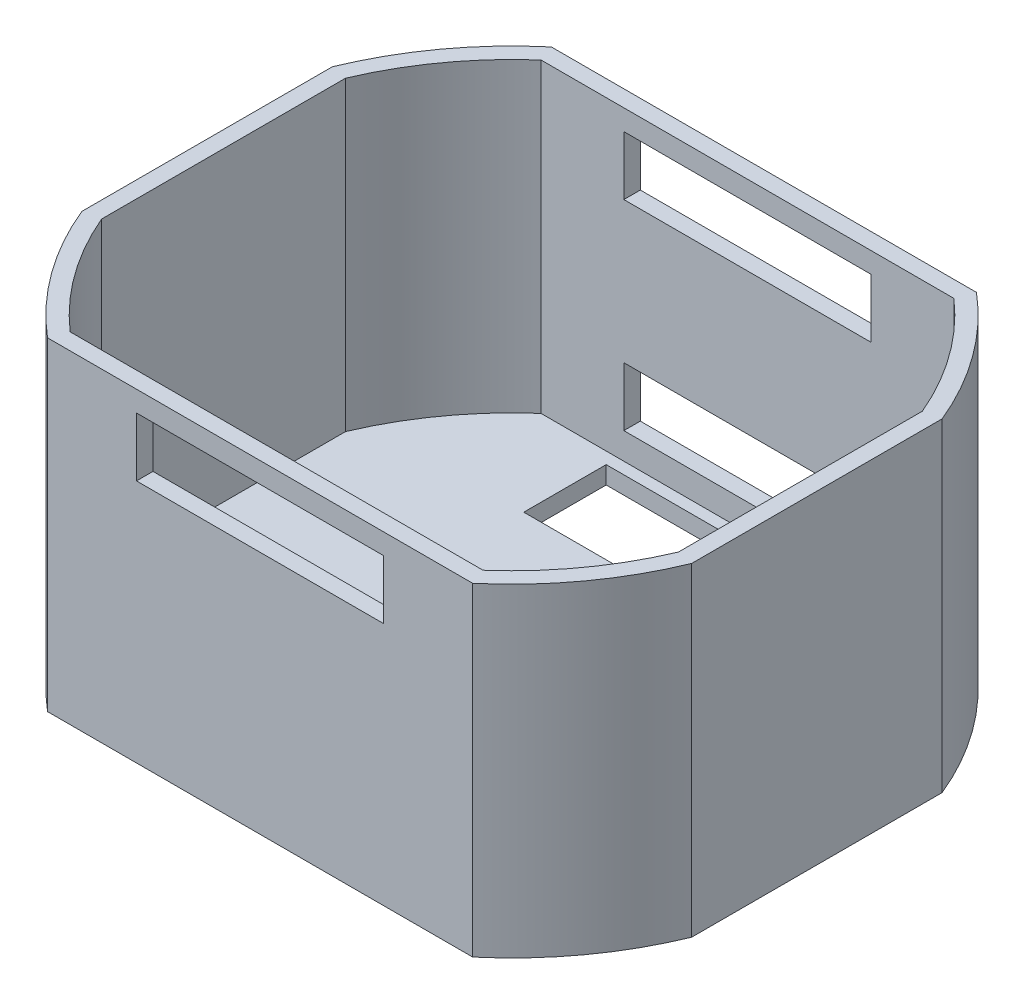
SolidWorks part; units mm, degrees
ref_plane "Front Plane" through (0, 0, 0) normal (0, 0, 1) x (1, 0, 0)
ref_plane "Top Plane" through (0, 0, 0) normal (0, 1, 0) x (1, 0, 0)
ref_plane "Right Plane" through (0, 0, 0) normal (1, 0, 0) x (0, 0, -1)
sketch "Sketch1" plane through (0, 0, 0) normal (0, 1, 0) x (1, 0, 0)
  line L0 (12.5, 21.5) -> (-12.5, 21.5) construction
  line L1 (12.5, -20) -> (-12.5, -20) construction
  line L2 (24.5, -8) -> (24.5, 8) construction
  line L3 (12.5, 20) -> (-12.5, 20) construction
  line L4 (-24.5, -8) -> (-24.5, 8) construction
  line L5 (24.5, -20) -> (-24.5, 20) construction
  line L6 (24.5, 20) -> (-24.5, -20) construction
  line L7 (26, -8) -> (26, 8) construction
  line L8 (12.5, -21.5) -> (-12.5, -21.5) construction
  line L9 (-26, -8) -> (-26, 8) construction
  line L10 (-26, 8) -> (-26, -8) construction
  line L11 (-12.5, -21.5) -> (12.5, -21.5) construction
  line L12 (26, -8) -> (26, 8) construction
  line L13 (12.5, 21.5) -> (-12.5, 21.5) construction
  line L14 (-17.5374, 20) -> (17.5374, 20)
  line L15 (-24.5, 10.3591) -> (-24.5, -10.3591)
  line L16 (0, 38.2323) -> (0, -51.2304) construction
  line L17 (24.5, 10.3591) -> (24.5, -10.3591)
  line L18 (-36.4719, 0) -> (42.8696, 0) construction
  line L19 (-17.5374, -20) -> (17.5374, -20)
  line L20 (-18.0566, 21.4) -> (18.0566, 21.4)
  line L21 (25.9, 10.6391) -> (25.9, -10.6391)
  line L22 (-18.0566, -21.4) -> (18.0566, -21.4)
  line L23 (-25.9, 10.6391) -> (-25.9, -10.6391)
  arc A0 (12.5, 20) -> (24.5, 8) centre (12.5, 8) cw construction
  arc A1 (24.5, -8) -> (12.5, -20) centre (12.5, -8) cw construction
  arc A2 (-12.5, -20) -> (-24.5, -8) centre (-12.5, -8) cw construction
  arc A3 (-24.5, 8) -> (-12.5, 20) centre (-12.5, 8) cw construction
  arc A4 (-26, 8) -> (-21.1, 18.4062) centre (-12.5, 8) cw construction
  arc A5 (12.5, 21.5) -> (26, 8) centre (12.5, 8) cw construction
  arc A6 (26, -8) -> (12.5, -21.5) centre (12.5, -8) cw construction
  arc A7 (-12.5, -21.5) -> (-26, -8) centre (-12.5, -8) cw construction
  arc A8 (-12.5, 21.5) -> (-16.4382, 20.9128) centre (-12.5, 8) ccw construction
  arc A9 (-26, -8) -> (-12.5, -21.5) centre (-12.5, -8) ccw construction
  arc A10 (12.5, -21.5) -> (26, -8) centre (12.5, -8) ccw construction
  arc A11 (26, 8) -> (12.5, 21.5) centre (12.5, 8) ccw construction
  arc A13 (24.5, 10.3591) -> (17.5374, 20) centre (0, 0) ccw
  arc A14 (26, 5.6178) -> (24.5, 10.3591) centre (0, 0) ccw construction
  arc A16 (26, -5.6178) -> (26, 5.6178) centre (0, 0) ccw construction
  arc A17 (24.5, -10.3591) -> (26, -5.6178) centre (0, 0) ccw construction
  arc A18 (-16.4382, -20.9128) -> (0, -26.6) centre (0, 0) ccw construction
  arc A19 (17.5374, -20) -> (24.5, -10.3591) centre (0, 0) ccw
  arc A20 (-17.5374, -20) -> (-16.4382, -20.9128) centre (0, 0) ccw construction
  arc A21 (0, -26.6) -> (16.4382, -20.9128) centre (0, 0) ccw construction
  arc A22 (16.4382, -20.9128) -> (17.5374, -20) centre (0, 0) ccw construction
  arc A23 (-24.5, 10.3591) -> (-26, 5.6178) centre (0, 0) ccw construction
  arc A24 (-26.6, 0) -> (-26, -5.6178) centre (0, 0) ccw construction
  arc A25 (-26, 5.6178) -> (-26.6, 0) centre (0, 0) ccw construction
  arc A26 (-26, -5.6178) -> (-24.5, -10.3591) centre (0, 0) ccw construction
  arc A27 (-24.5, -10.3591) -> (-17.5374, -20) centre (0, 0) ccw
  arc A28 (0, 26.6) -> (-16.4382, 20.9128) centre (0, 0) ccw construction
  arc A29 (-17.5374, 20) -> (-24.5, 10.3591) centre (0, 0) ccw
  arc A30 (-26, 8) -> (-12.5, 21.5) centre (-12.5, 8) cw construction
  arc A31 (-16.4382, 20.9128) -> (-17.5374, 20) centre (0, 0) ccw construction
  arc A32 (-16.4382, 20.9128) -> (-21.1, 18.4062) centre (-12.5, 8) ccw construction
  arc A33 (-21.1, 18.4062) -> (-26, 8) centre (-12.5, 8) ccw construction
  arc A34 (-21.1, 18.4062) -> (-16.4382, 20.9128) centre (-12.5, 8) cw construction
  arc A35 (-16.4382, 20.9128) -> (-16.3829, 20.9295) centre (-12.5, 8) cw construction
  arc A36 (17.5374, 20) -> (16.4382, 20.9128) centre (0, 0) ccw construction
  arc A37 (16.4382, 20.9128) -> (0, 26.6) centre (0, 0) ccw construction
  arc A38 (25.9, 10.6391) -> (18.0566, 21.4) centre (0, 0) ccw
  arc A39 (18.0566, -21.4) -> (25.9, -10.6391) centre (0, 0) ccw
  arc A40 (-25.9, -10.6391) -> (-18.0566, -21.4) centre (0, 0) ccw
  arc A41 (-18.0566, 21.4) -> (-25.9, 10.6391) centre (0, 0) ccw
  point P0 (0, 0)
  point P33 (26, 0)
  point P43 (-26, 0)
  point P44 (0, 21.5)
  dimension "D3" = 12
  dimension "D6" = 26.6
  dimension "D1" = 40
  dimension "D2" = 49
  dimension "D5" = 16
  dimension "D8" = 49
  dimension "D9" = 40
  dimension "D4" = 1.5
  dimension "D10" = 1.4
extrude "Boss-Extrude1" add sketch "Sketch1" along normal mid plane 27.5
sketch "Sketch2" plane through (0, 0, -20) normal (0, 0, 1) x (1, 0, 0)
  line L0 (0, 17.4955) -> (0, -16.8165) construction
  line L1 (-10.5, 12) -> (10.5, 12)
  line L2 (-10.5, 12) -> (-10.5, 7)
  line L3 (-10.5, 7) -> (10.5, 7)
  line L4 (10.5, 12) -> (10.5, 7)
  line L5 (-10.5, 12) -> (10.5, 7) construction
  line L6 (-10.5, 7) -> (10.5, 12) construction
  line L7 (-29.7868, 0) -> (39.3953, 0) construction
  point P0 (0, 9.5)
  dimension "D1" = 21
  dimension "D2" = 5
  dimension "D3" = 9.5
extrude "Cut-Extrude1" cut sketch "Sketch2" against normal through all both and the other way through all
sketch "Sketch3" plane through (0, -13.75, 0) normal (0, -1, 0) x (1, 0, 0)
  line L18 (-18.0566, -21.4) -> (18.0566, -21.4)
  line L19 (25.9, -10.6391) -> (25.9, 10.6391)
  line L20 (18.0566, 21.4) -> (-18.0566, 21.4)
  line L21 (-25.9, 10.6391) -> (-25.9, -10.6391)
  line L22 (-18.0566, -21.4) -> (18.0566, -21.4)
  line L23 (25.9, -10.6391) -> (25.9, 10.6391)
  line L24 (18.0566, 21.4) -> (-18.0566, 21.4)
  line L25 (-25.9, 10.6391) -> (-25.9, -10.6391)
  arc A20 (-25.9, -10.6391) -> (-18.0566, -21.4) centre (0, 0) ccw
  arc A21 (18.0566, -21.4) -> (25.9, -10.6391) centre (0, 0) ccw
  arc A22 (25.9, 10.6391) -> (18.0566, 21.4) centre (0, 0) ccw
  arc A23 (-18.0566, 21.4) -> (-25.9, 10.6391) centre (0, 0) ccw
  arc A24 (-25.9, -10.6391) -> (-18.0566, -21.4) centre (0, 0) ccw
  arc A25 (18.0566, -21.4) -> (25.9, -10.6391) centre (0, 0) ccw
  arc A26 (25.9, 10.6391) -> (18.0566, 21.4) centre (0, 0) ccw
  arc A27 (-18.0566, 21.4) -> (-25.9, 10.6391) centre (0, 0) ccw
  dimension "D1" = 0
extrude "Boss-Extrude2" add sketch "Sketch3" against normal blind 1.5
sketch "Sketch4" plane through (0, 0, -21.4) normal (0, 0, -1) x (-1, 0, 0)
  line L5 (-10.5, -5) -> (10.5, -5)
  line L6 (-10.5, -5) -> (-10.5, -10)
  line L7 (-10.5, -10) -> (10.5, -10)
  line L9 (10.5, -5) -> (10.5, -10)
  line L10 (-10.5, -5) -> (10.5, -10) construction
  line L11 (-10.5, -10) -> (10.5, -5) construction
  point P0 (0, -7.5)
  dimension "D1" = 5
  dimension "D2" = 21
  dimension "D3" = 7.5
extrude "Cut-Extrude2" cut sketch "Sketch4" against normal blind 2
sketch "Sketch5" plane through (0, -12.25, 0) normal (0, 1, 0) x (-1, 0, 0)
  line L0 (-24.3987, 0) -> (22.5042, 0) construction
  line L5 (-11, 19) -> (11, 12) construction
  line L6 (-11, 12) -> (11, 19) construction
  line L7 (-11, -12) -> (11, -12)
  line L8 (11, -19) -> (11, -12)
  line L9 (-11, -19) -> (11, -19)
  line L10 (-11, -19) -> (-11, -12)
  point P0 (0, 15.5)
  dimension "D1" = 7
  dimension "D2" = 22
  dimension "D3" = 15.5
extrude "Cut-Extrude3" cut sketch "Sketch5" against normal blind 2
